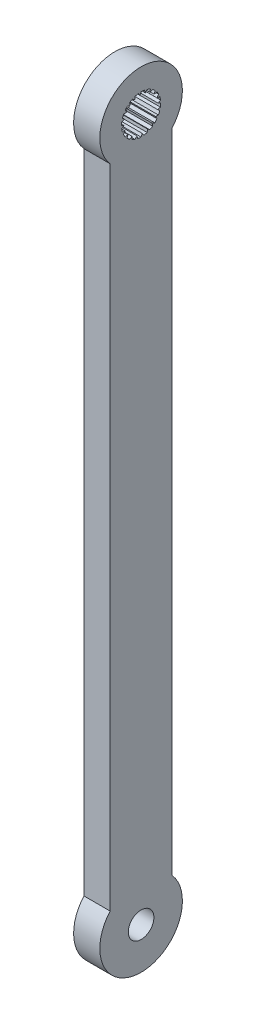
SolidWorks part; units mm, degrees
ref_plane "Front Plane" through (0, 0, 0) normal (0, 0, 1) x (1, 0, 0)
ref_plane "Top Plane" through (0, 0, 0) normal (0, 1, 0) x (1, 0, 0)
ref_plane "Right Plane" through (0, 0, 0) normal (1, 0, 0) x (0, 0, -1)
sketch "Sketch1" plane through (0, 0, 0) normal (1, 0, 0) x (0, 0, -1)
  line L0 (0, 0) -> (-3.75, -3.3072) construction
  line L2 (3.75, -3.3072) -> (3.75, -81.6928)
  line L3 (3.75, -81.6928) -> (-3.75, -81.6928) construction
  line L4 (-3.75, -3.3072) -> (-3.75, -81.6928)
  line L5 (3.75, -3.3072) -> (-3.75, -3.3072) construction
  line L6 (0, 0) -> (3.75, -3.3072) construction
  line L48 (-1.7544, 1.0965) -> (-2.0991, 1.111)
  line L49 (-1.9185, 1.4) -> (-1.7544, 1.0965)
  line L50 (-1.3297, 1.585) -> (-1.6531, 1.7053)
  line L51 (-1.3919, 1.9243) -> (-1.3297, 1.585)
  line L52 (-0.7748, 1.9183) -> (-1.0452, 2.1326)
  line L53 (-0.7292, 2.2603) -> (-0.7748, 1.9183)
  line L54 (-0.1441, 2.0639) -> (-0.335, 2.3513)
  line L55 (0.005, 2.375) -> (-0.1441, 2.0639)
  line L56 (0.5007, 2.0074) -> (0.408, 2.3397)
  line L57 (0.7387, 2.2572) -> (0.5007, 2.0074)
  line L58 (1.0965, 1.7544) -> (1.111, 2.0991)
  line L59 (1.4, 1.9185) -> (1.0965, 1.7544)
  line L60 (1.585, 1.3297) -> (1.7053, 1.6531)
  line L61 (1.9243, 1.3919) -> (1.585, 1.3297)
  line L62 (1.9183, 0.7748) -> (2.1326, 1.0452)
  line L63 (2.2603, 0.7292) -> (1.9183, 0.7748)
  line L64 (2.0639, 0.1441) -> (2.3513, 0.335)
  line L65 (2.375, -0.005) -> (2.0639, 0.1441)
  line L66 (2.0074, -0.5007) -> (2.3397, -0.408)
  line L67 (2.2572, -0.7387) -> (2.0074, -0.5007)
  line L68 (1.7544, -1.0965) -> (2.0991, -1.111)
  line L69 (1.9185, -1.4) -> (1.7544, -1.0965)
  line L70 (1.3297, -1.585) -> (1.6531, -1.7053)
  line L71 (1.3919, -1.9243) -> (1.3297, -1.585)
  line L72 (0.7748, -1.9183) -> (1.0452, -2.1326)
  line L73 (0.7292, -2.2603) -> (0.7748, -1.9183)
  line L74 (0.1441, -2.0639) -> (0.335, -2.3513)
  line L75 (-0.005, -2.375) -> (0.1441, -2.0639)
  line L76 (-0.5007, -2.0074) -> (-0.408, -2.3397)
  line L77 (-0.7387, -2.2572) -> (-0.5007, -2.0074)
  line L78 (-1.0965, -1.7544) -> (-1.111, -2.0991)
  line L79 (-1.4, -1.9185) -> (-1.0965, -1.7544)
  line L80 (-1.585, -1.3297) -> (-1.7053, -1.6531)
  line L81 (-1.9243, -1.3919) -> (-1.585, -1.3297)
  line L82 (-1.9183, -0.7748) -> (-2.1326, -1.0452)
  line L83 (-2.2603, -0.7292) -> (-1.9183, -0.7748)
  line L84 (-2.0639, -0.1441) -> (-2.3513, -0.335)
  line L85 (-2.375, 0.005) -> (-2.0639, -0.1441)
  line L86 (-2.0074, 0.5007) -> (-2.3397, 0.408)
  line L87 (-2.2572, 0.7387) -> (-2.0074, 0.5007)
  line L88 (-1.7544, 1.0965) -> (-2.0991, 1.111)
  line L89 (-1.9185, 1.4) -> (-1.7544, 1.0965)
  line L90 (-1.3297, 1.585) -> (-1.6531, 1.7053)
  line L91 (-1.3919, 1.9243) -> (-1.3297, 1.585)
  line L92 (-0.7748, 1.9183) -> (-1.0452, 2.1326)
  line L93 (-0.7292, 2.2603) -> (-0.7748, 1.9183)
  line L94 (-0.1441, 2.0639) -> (-0.335, 2.3513)
  line L95 (0.005, 2.375) -> (-0.1441, 2.0639)
  line L96 (0.5007, 2.0074) -> (0.408, 2.3397)
  line L97 (0.7387, 2.2572) -> (0.5007, 2.0074)
  line L98 (1.0965, 1.7544) -> (1.111, 2.0991)
  line L99 (1.4, 1.9185) -> (1.0965, 1.7544)
  line L100 (1.585, 1.3297) -> (1.7053, 1.6531)
  line L101 (1.9243, 1.3919) -> (1.585, 1.3297)
  line L102 (1.9183, 0.7748) -> (2.1326, 1.0452)
  line L103 (2.2603, 0.7292) -> (1.9183, 0.7748)
  line L104 (2.0639, 0.1441) -> (2.3513, 0.335)
  line L105 (2.375, -0.005) -> (2.0639, 0.1441)
  line L106 (2.0074, -0.5007) -> (2.3397, -0.408)
  line L107 (2.2572, -0.7387) -> (2.0074, -0.5007)
  line L108 (1.7544, -1.0965) -> (2.0991, -1.111)
  line L109 (1.9185, -1.4) -> (1.7544, -1.0965)
  line L110 (1.3297, -1.585) -> (1.6531, -1.7053)
  line L111 (1.3919, -1.9243) -> (1.3297, -1.585)
  line L112 (0.7748, -1.9183) -> (1.0452, -2.1326)
  line L113 (0.7292, -2.2603) -> (0.7748, -1.9183)
  line L114 (0.1441, -2.0639) -> (0.335, -2.3513)
  line L115 (-0.005, -2.375) -> (0.1441, -2.0639)
  line L116 (-0.5007, -2.0074) -> (-0.408, -2.3397)
  line L117 (-0.7387, -2.2572) -> (-0.5007, -2.0074)
  line L118 (-1.0965, -1.7544) -> (-1.111, -2.0991)
  line L119 (-1.4, -1.9185) -> (-1.0965, -1.7544)
  line L120 (-1.585, -1.3297) -> (-1.7053, -1.6531)
  line L121 (-1.9243, -1.3919) -> (-1.585, -1.3297)
  line L122 (-1.9183, -0.7748) -> (-2.1326, -1.0452)
  line L123 (-2.2603, -0.7292) -> (-1.9183, -0.7748)
  line L124 (-2.0639, -0.1441) -> (-2.3513, -0.335)
  line L125 (-2.375, 0.005) -> (-2.0639, -0.1441)
  line L126 (-2.0074, 0.5007) -> (-2.3397, 0.408)
  line L127 (-2.2572, 0.7387) -> (-2.0074, 0.5007)
  arc A1 (3.75, -3.3072) -> (-3.75, -3.3072) centre (0, 0) ccw
  arc A2 (-3.75, -81.6928) -> (3.75, -81.6928) centre (0, -85) ccw
  circle A3 centre (0, -85) radius 1.55
  arc A24 (-1.6531, 1.7053) -> (-1.9185, 1.4) centre (0, 0) ccw
  arc A25 (-1.0452, 2.1326) -> (-1.3919, 1.9243) centre (0, 0) ccw
  arc A26 (-0.335, 2.3513) -> (-0.7292, 2.2603) centre (0, 0) ccw
  arc A27 (0.408, 2.3397) -> (0.005, 2.375) centre (0, 0) ccw
  arc A28 (1.111, 2.0991) -> (0.7387, 2.2572) centre (0, 0) ccw
  arc A29 (1.7053, 1.6531) -> (1.4, 1.9185) centre (0, 0) ccw
  arc A30 (2.1326, 1.0452) -> (1.9243, 1.3919) centre (0, 0) ccw
  arc A31 (2.3513, 0.335) -> (2.2603, 0.7292) centre (0, 0) ccw
  arc A32 (2.3397, -0.408) -> (2.375, -0.005) centre (0, 0) ccw
  arc A33 (2.0991, -1.111) -> (2.2572, -0.7387) centre (0, 0) ccw
  arc A34 (1.6531, -1.7053) -> (1.9185, -1.4) centre (0, 0) ccw
  arc A35 (1.0452, -2.1326) -> (1.3919, -1.9243) centre (0, 0) ccw
  arc A36 (0.335, -2.3513) -> (0.7292, -2.2603) centre (0, 0) ccw
  arc A37 (-0.408, -2.3397) -> (-0.005, -2.375) centre (0, 0) ccw
  arc A38 (-1.111, -2.0991) -> (-0.7387, -2.2572) centre (0, 0) ccw
  arc A39 (-1.7053, -1.6531) -> (-1.4, -1.9185) centre (0, 0) ccw
  arc A40 (-2.1326, -1.0452) -> (-1.9243, -1.3919) centre (0, 0) ccw
  arc A41 (-2.3513, -0.335) -> (-2.2603, -0.7292) centre (0, 0) ccw
  arc A42 (-2.3397, 0.408) -> (-2.375, 0.005) centre (0, 0) ccw
  arc A43 (-2.0991, 1.111) -> (-2.2572, 0.7387) centre (0, 0) ccw
  arc A44 (-1.6531, 1.7053) -> (-1.9185, 1.4) centre (0, 0) ccw
  arc A45 (-1.0452, 2.1326) -> (-1.3919, 1.9243) centre (0, 0) ccw
  arc A46 (-0.335, 2.3513) -> (-0.7292, 2.2603) centre (0, 0) ccw
  arc A47 (0.408, 2.3397) -> (0.005, 2.375) centre (0, 0) ccw
  arc A48 (1.111, 2.0991) -> (0.7387, 2.2572) centre (0, 0) ccw
  arc A49 (1.7053, 1.6531) -> (1.4, 1.9185) centre (0, 0) ccw
  arc A50 (2.1326, 1.0452) -> (1.9243, 1.3919) centre (0, 0) ccw
  arc A51 (2.3513, 0.335) -> (2.2603, 0.7292) centre (0, 0) ccw
  arc A52 (2.3397, -0.408) -> (2.375, -0.005) centre (0, 0) ccw
  arc A53 (2.0991, -1.111) -> (2.2572, -0.7387) centre (0, 0) ccw
  arc A54 (1.6531, -1.7053) -> (1.9185, -1.4) centre (0, 0) ccw
  arc A55 (1.0452, -2.1326) -> (1.3919, -1.9243) centre (0, 0) ccw
  arc A56 (0.335, -2.3513) -> (0.7292, -2.2603) centre (0, 0) ccw
  arc A57 (-0.408, -2.3397) -> (-0.005, -2.375) centre (0, 0) ccw
  arc A58 (-1.111, -2.0991) -> (-0.7387, -2.2572) centre (0, 0) ccw
  arc A59 (-1.7053, -1.6531) -> (-1.4, -1.9185) centre (0, 0) ccw
  arc A60 (-2.1326, -1.0452) -> (-1.9243, -1.3919) centre (0, 0) ccw
  arc A61 (-2.3513, -0.335) -> (-2.2603, -0.7292) centre (0, 0) ccw
  arc A62 (-2.3397, 0.408) -> (-2.375, 0.005) centre (0, 0) ccw
  arc A63 (-2.0991, 1.111) -> (-2.2572, 0.7387) centre (0, 0) ccw
  dimension "D1" = 0
  dimension "D2" = 10
  dimension "D4" = 10
  dimension "D6" = 3.1
  dimension "D3" = 7.5
  dimension "D5" = 85
extrude "Boss-Extrude3" add sketch "Sketch1" along normal blind 3.175
